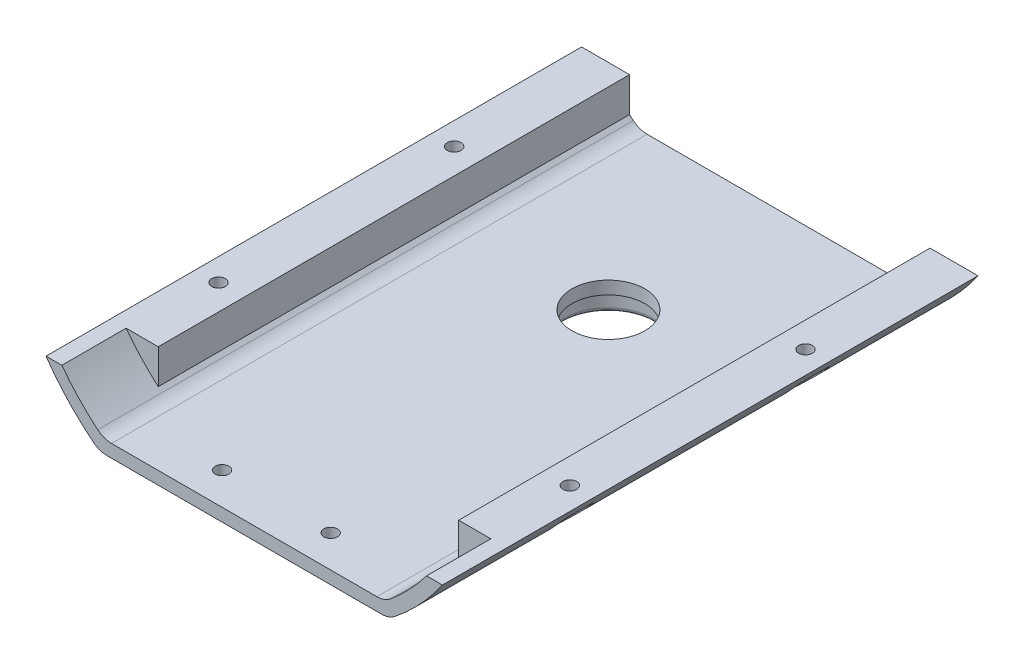
SolidWorks part; units mm, degrees
material "ABS PC"
ref_plane "Ön Düzlem" through (0, 0, 0) normal (0, 0, 1) x (1, 0, 0)
ref_plane "Üst Düzlem" through (0, 0, 0) normal (0, 1, 0) x (1, 0, 0)
ref_plane "Sağ Düzlem" through (0, 0, 0) normal (1, 0, 0) x (0, 0, -1)
sketch "Çizim1" plane through (0, 0, 0) normal (0, 0, 1) x (1, 0, 0)
  line L0 (-35.0625, -32) -> (-42.5625, -32)
  line L2 (0, -42) -> (0, -45) construction
  line L3 (-32.04, -45) -> (32.04, -45)
  line L4 (-30.9687, -42) -> (30.9687, -42)
  line L6 (-32.7347, -42) -> (32.7347, -42) construction
  line L7 (-33.75, -45) -> (33.75, -45) construction
  line L9 (0, 0) -> (0.1361, 0) construction
  line L10 (0.1361, -32) -> (0, -32)
  line L11 (35.0625, -32) -> (42.5625, -32)
  line L12 (-35.0625, -32) -> (-35.0625, -40.0773)
  line L13 (35.0625, -32) -> (35.0625, -40.0773)
  line L14 (-42.5625, -32) -> (-46.2608, -32)
  line L15 (42.5625, -32) -> (46.2608, -32)
  line L16 (33.75, 45) -> (-33.75, 45) construction
  line L17 (32.7347, 42) -> (-32.7347, 42) construction
  arc A0 (-46.2608, -32) -> (-35.1659, -43.9024) centre (0, 0) ccw
  arc A1 (35.1659, -43.9024) -> (46.2608, -32) centre (0, 0) ccw
  arc A2 (34.1779, -40.8342) -> (35.0625, -40.0773) centre (0, 0) ccw
  arc A3 (-35.0625, -40.0773) -> (-34.1779, -40.8342) centre (0, 0) ccw
  arc A4 (32.7347, -42) -> (32.7347, 42) centre (0, 0) ccw construction
  arc A5 (30.9687, -42) -> (34.1779, -40.8342) centre (30.9687, -37) ccw
  arc A6 (33.75, -45) -> (33.75, 45) centre (0, 0) ccw construction
  arc A7 (32.04, -45) -> (35.1659, -43.9024) centre (32.04, -40) ccw
  arc A8 (-32.7347, 42) -> (-32.7347, -42) centre (0, 0) ccw construction
  arc A9 (-30.9687, -42) -> (-34.1779, -40.8342) centre (-30.9687, -37) cw
  arc A10 (-33.75, 45) -> (-33.75, -45) centre (0, 0) ccw construction
  arc A11 (-32.04, -45) -> (-35.1659, -43.9024) centre (-32.04, -40) cw
  point P7 (0, 45)
  point P11 (0, -45)
  point P22 (33.75, -45)
  dimension "D1" = 112.5
  dimension "D4" = 5
  dimension "D5" = 32
  dimension "D6" = 7.5
  dimension "D7" = 7.5
  dimension "D3" = 3
extrude "Yükseklik-Ekstrüzyon1" add sketch "Çizim1" along normal blind 125 contours A11 L3 A7 A1 L15 L11 L13 A2 A5 L4 A9 A3 L12 L0 L14 A0
sketch "Çizim2" plane through (0, 0, 125) normal (0, 0, 1) x (1, 0, 0)
  line L0 (30.9687, -42) -> (-30.9687, -42)
  arc A0 (34.1779, -40.8342) -> (-34.1779, -40.8342) centre (0, 0) ccw
  arc A1 (34.1779, -40.8342) -> (30.9687, -42) centre (30.9687, -37) cw
  arc A2 (-30.9687, -42) -> (-34.1779, -40.8342) centre (-30.9687, -37) cw
  point P6 (0, -42)
  dimension "D1" = 106.5
  dimension "D3" = 5
  dimension "D4" = 5
  dimension "D2" = 42
extrude "Kes-Ekstrüzyon1" cut sketch "Çizim2" against normal blind 15
sketch "Çizim3" plane through (0, -45, 0) normal (0, -1, 0) x (1, 0, 0)
  line L4 (-12.67, 117.5) -> (-12.67, 125) construction
  line L5 (-32.04, 125) -> (32.04, 125) construction
  line L7 (12.67, 117.5) -> (12.67, 125) construction
sketch "Çizim7" plane through (0, -45, 0) normal (0, -1, 0) x (-1, 0, 0)
  point P0 (-12.67, -117.5)
  point P3 (12.67, -117.5)
hole_wizard "M3 Boşluklu Delik1" positions "Çizim7" profile "Çizim6" hole size "M3" standard "ISO"
sketch "Çizim6" plane through (12.67, -45, 117.5) normal (1, 0, 0) x (0, 0, -1)
  line L0 (0, 0) -> (0, 12.4614)
  line L1 (0, 12.4614) -> (1.6, 11.5)
  line L2 (1.6, 11.5) -> (1.6, 0)
  line L5 (1.6, 0) -> (0, 0)
  line L10 (0, 12.4614) -> (-1.6, 11.5) construction
  line L11 (0, -6.35) -> (0, 107.95) construction
  dimension "Hole Dia." = 3.2
  dimension "Hole Depth" = 11.5
  dimension "Drill Angle" = 118
sketch "Çizim8" plane through (0, -45, 0) normal (0, -1, 0) x (1, 0, 0)
  line L0 (0, 125) -> (0, 90) construction
  line L1 (-32.04, 125) -> (32.04, 125) construction
  line L2 (0, 0) -> (0, 35) construction
  line L3 (41, 90) -> (-41, 90) construction
  line L4 (41, 35) -> (-41, 35) construction
  circle A0 centre (-41, 90) radius 4
  circle A1 centre (41, 90) radius 4
  circle A2 centre (-41, 35) radius 4
  circle A3 centre (41, 35) radius 4
  dimension "D5" = 8
  dimension "D6" = 8
  dimension "D1" = 35
  dimension "D2" = 35
  dimension "D3" = 41
  dimension "D4" = 41
extrude "Kes-Ekstrüzyon2" cut sketch "Çizim8" against normal blind 9
hole_wizard "M3 Boşluklu Delik2" positions "3B Çizim1" profile "Çizim9" hole size "M3" standard "ISO"
sketch3d "3B Çizim1"
  line L0 (-41, -36, 90) -> (-41, -42.3682, 90) construction
  line L1 (-41, -36, 35) -> (-41, -42.3682, 35) construction
  line L2 (41, -36, 90) -> (41, -42.3682, 90) construction
  line L3 (41, -36, 35) -> (41, -42.3682, 35) construction
  point P0 (-41, -36, 90)
  point P4 (-41, -36, 35)
  point P8 (41, -36, 90)
  point P12 (41, -36, 35)
sketch "Çizim9" plane through (-41, -36, 90) normal (1, 0, 0) x (0, 0, -1)
  line L0 (0, 0) -> (0, 12.4614)
  line L1 (0, 12.4614) -> (1.6, 11.5)
  line L2 (1.6, 11.5) -> (1.6, 0)
  line L5 (1.6, 0) -> (0, 0)
  line L10 (0, 12.4614) -> (-1.6, 11.5) construction
  line L11 (0, -6.35) -> (0, 107.95) construction
  dimension "Hole Dia." = 3.2
  dimension "Hole Depth" = 11.5
  dimension "Drill Angle" = 118
sketch "Çizim10" plane through (0, 0, 0) normal (0, 0, -1) x (-1, 0, 0)
  line L0 (0, 0) -> (-24.9353, 0) construction
  line L1 (0, 0) -> (-38.3384, -35.1307) construction
  line L2 (0, 0) -> (38.3384, -35.1307) construction
  line L3 (0, 0) -> (14.1453, 0) construction
  point P6 (-38.3384, -35.1307)
  point P7 (38.3384, -35.1307)
  point P11 (-38.3384, -35.1307)
  point P15 (38.3384, -35.1307)
  dimension "D1" = 52
  dimension "D2" = 42.5
  dimension "D3" = 42.5
  dimension "D4" = 52
hole_wizard "M3x0.5 Helisarmal İçin Dişli Delik1" positions "Çizim10" profile "Çizim11" tap size "M3x0.5" standard "Helicoil® Metric"
sketch "Çizim11" plane through (-38.3384, -35.1307, 0) normal (1, 0, 0) x (0, 1, 0)
  line L0 (0, 0) -> (0, 9.9464)
  line L1 (0, 9.9464) -> (1.575, 9)
  line L2 (1.575, 9) -> (1.575, 0)
  line L5 (1.575, 0) -> (0, 0)
  line L10 (0, 9.9464) -> (-1.575, 9) construction
  line L11 (0, -6.35) -> (0, 107.95) construction
  dimension "Tap Drill Dia." = 3.15
  dimension "Tap Drill Depth" = 9
  dimension "Drill Angle" = 118
cosmetic thread "Delik Dişi1" parameters "D1"=3.5, "D2"=3.716
cosmetic thread "Delik Dişi2" parameters "D1"=3.5, "D2"=3.716
sketch "Çizim13" plane through (0, -45, 0) normal (0, -1, 0) x (1, 0, 0)
  line L0 (0, 125) -> (0, 40) construction
  line L1 (-32.04, 125) -> (32.04, 125) construction
  circle A0 centre (0, 40) radius 8.5
  dimension "D2" = 17
  dimension "D1" = 85
extrude "Kes-Ekstrüzyon3" cut sketch "Çizim13" against normal blind 10
sketch "Çizim14" plane through (0, -45, 0) normal (0, -1, 0) x (1, 0, 0)
  line L0 (0, 125) -> (0, 40) construction
  line L1 (-32.04, 125) -> (32.04, 125) construction
  circle A0 centre (0, 40) radius 10.5
  circle A1 centre (0, 40) radius 13.5
  dimension "D1" = 21
  dimension "D2" = 3
extrude "Yükseklik-Ekstrüzyon2" add sketch "Çizim14" along normal blind 5
fillet "Radyus1" radius 1 3 edges at (0, -50, 29.5) (0, -50, 26.5) (0, -45, 53.5)
